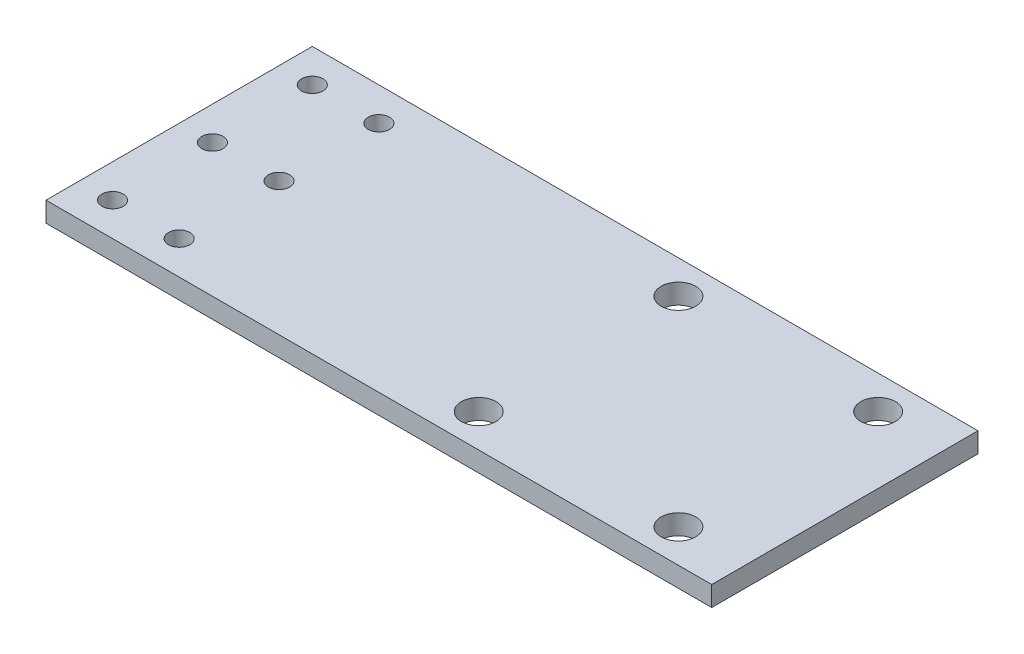
SolidWorks part; units mm, degrees
ref_plane "前视基准面" through (0, 0, 0) normal (0, 0, 1) x (1, 0, 0)
ref_plane "上视基准面" through (0, 0, 0) normal (0, 1, 0) x (1, 0, 0)
ref_plane "右视基准面" through (0, 0, 0) normal (1, 0, 0) x (0, 0, -1)
other "Configuration Table"
sketch "草图1" plane through (0, 0, 0) normal (0, 1, 0) x (1, 0, 0)
  line L0 (20, -20) -> (0, -20) construction
  line L1 (0, 0) -> (100, 0)
  line L2 (0, 0) -> (0, -40)
  line L3 (0, -40) -> (100, -40)
  line L4 (100, 0) -> (100, -40)
  line L5 (0, -40) -> (20, -40) construction
  line L6 (0, -40) -> (0, 0) construction
  line L7 (0, 0) -> (20, 0) construction
  line L8 (20, -40) -> (20, 0) construction
  line L9 (10, -20) -> (10, 0) construction
  line L10 (5, -5) -> (5, -20) construction
  circle A0 centre (5, -20) radius 1.6
  circle A1 centre (5, -5) radius 1.6
  circle A2 centre (15, -20) radius 1.6
  circle A3 centre (15, -5) radius 1.6
  circle A4 centre (15, -35) radius 1.6
  circle A5 centre (5, -35) radius 1.6
  dimension "D4" = 3.2
  dimension "D5" = 3.2
  dimension "D1" = 40
  dimension "D2" = 100
  dimension "D3" = 20
  dimension "D6" = 5
  dimension "D7" = 15
extrude "凸台-拉伸1" add sketch "草图1" along normal blind 3
sketch "草图2" plane through (0, 3, 0) normal (0, 1, 0) x (1, 0, 0)
  line L0 (0, -40) -> (100, -40) construction
  line L1 (100, 0) -> (50, 0) construction
  line L2 (100, 0) -> (100, -40) construction
  line L3 (100, -40) -> (50, -40) construction
  line L4 (50, 0) -> (50, -40) construction
  line L5 (75, 0) -> (75, -40) construction
  line L6 (50, -20) -> (100, -20) construction
  circle A0 centre (60, -5) radius 2.6
  circle A1 centre (60, -35) radius 2.6
  circle A2 centre (90, -35) radius 2.6
  circle A3 centre (90, -5) radius 2.6
  dimension "D2" = 5.2
  dimension "D1" = 50
  dimension "D3" = 30
  dimension "D4" = 30
extrude "切除-拉伸1" cut sketch "草图2" against normal blind 3
